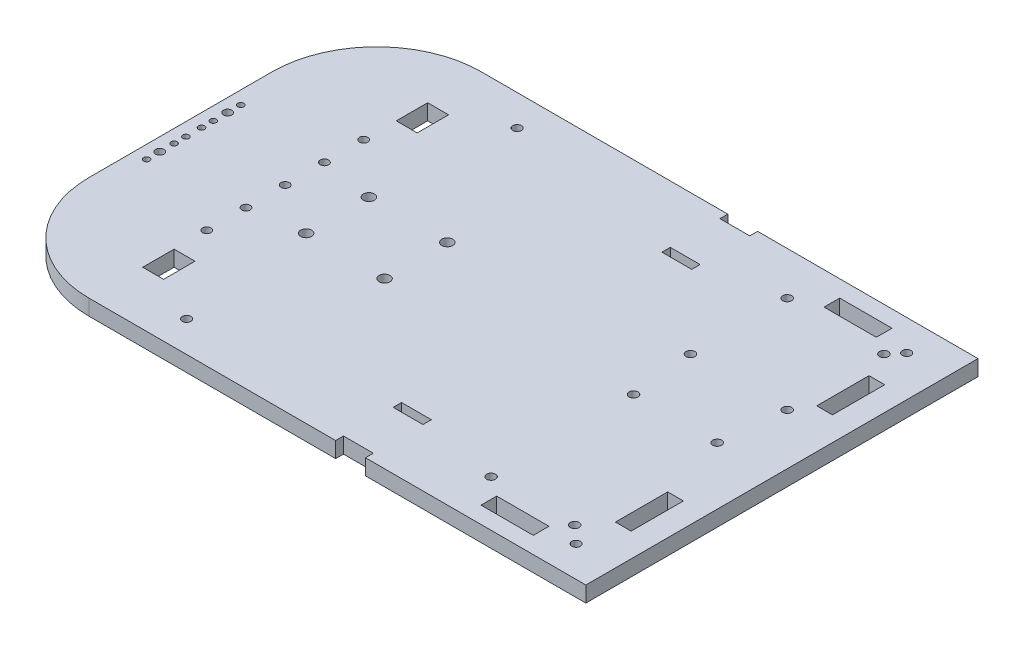
SolidWorks part; units mm, degrees
ref_plane "Front Plane" through (0, 0, 0) normal (0, 0, 1) x (1, 0, 0)
ref_plane "Top Plane" through (0, 0, 0) normal (0, 1, 0) x (1, 0, 0)
ref_plane "Right Plane" through (0, 0, 0) normal (1, 0, 0) x (0, 0, -1)
sketch "Sketch1" plane through (0, 0, 0) normal (0, 1, 0) x (1, 0, 0)
  line L1 (-115, 75) -> (115, 75)
  line L2 (-115, 75) -> (-115, -75)
  line L3 (-115, -75) -> (115, -75)
  line L4 (115, 75) -> (115, -75)
  line L5 (-115, 75) -> (115, -75) construction
  line L6 (-115, -75) -> (115, 75) construction
  point P0 (0, 0)
  dimension "D1" = 230
  dimension "D2" = 150
extrude "Boss-Extrude1" add sketch "Sketch1" along normal blind 6
sketch "Sketch2" plane through (0, 6, 0) normal (0, 1, 0) x (1, 0, 0)
  line L0 (115, 0) -> (-142.2059, 0) construction
  line L1 (115, -75) -> (115, 75) construction
  line L2 (-115, 0) -> (-80, 0) construction
  line L4 (-115, 75) -> (-115, -75) construction
  line L5 (115, 0) -> (25, 0) construction
  line L6 (25, 0) -> (25, -48.4236) construction
  line L7 (25, -75) -> (25, -72) construction
  line L8 (19.3, -72) -> (30.7, -72)
  line L9 (-115, -75) -> (115, -75) construction
  line L10 (25, -72) -> (25, -53) construction
  line L11 (19.3, -72) -> (19.3, -75)
  line L12 (19.3, -49.8) -> (30.7, -49.8)
  line L13 (19.3, -49.8) -> (19.3, -53)
  line L14 (19.3, -53) -> (30.7, -53)
  line L15 (30.7, -49.8) -> (30.7, -53)
  line L16 (19.3, -49.8) -> (30.7, -53) construction
  line L17 (19.3, -53) -> (30.7, -49.8) construction
  line L18 (19.3, -75) -> (30.7, -75)
  line L19 (30.7, -72) -> (30.7, -75)
  line L20 (19.3, -72) -> (30.7, -75) construction
  line L21 (19.3, -75) -> (30.7, -72) construction
  point P7 (25, -73.5)
  point P16 (25, -51.4)
  point P22 (25, -53)
  point P27 (25, -72)
  dimension "D1" = 35
  dimension "D2" = 90
  dimension "D3" = 3
  dimension "D4" = 19
  dimension "D5" = 3.2
  dimension "D6" = 11.4
  dimension "D7" = 3
  dimension "D8" = 11.4
extrude "Cut-Extrude1" cut sketch "Sketch2" against normal blind 26
mirror "Mirror1" about plane through (0, 0, 0) normal (0, 0, 1) of "Cut-Extrude1"
sketch "Sketch3" plane through (0, 6, 0) normal (0, 1, 0) x (1, 0, 0)
  line L0 (-115, 0) -> (112.5797, 0) construction
  line L1 (-115, 75) -> (-115, -75) construction
  line L3 (-55, 12) -> (-25, 12) construction
  line L4 (-55, 12) -> (-55, -12) construction
  line L5 (-55, -12) -> (-25, -12) construction
  line L6 (-25, 12) -> (-25, -12) construction
  line L7 (-55, 12) -> (-25, -12) construction
  line L8 (-55, -12) -> (-25, 12) construction
  circle A0 centre (-25, -12) radius 2.1
  circle A1 centre (-25, 12) radius 2.1
  circle A2 centre (-55, 12) radius 2.1
  circle A3 centre (-55, -12) radius 2.1
  point P5 (-40, 0)
  dimension "D4" = 4.2
  dimension "D5" = 4.2
  dimension "D1" = 30
  dimension "D2" = 24
  dimension "D3" = 60
extrude "Cut-Extrude2" cut sketch "Sketch3" against normal blind 26
sketch "Sketch4" plane through (0, 6, 0) normal (0, 1, 0) x (1, 0, 0)
  line L0 (-115, 0) -> (-75, 0) construction
  line L1 (-115, 75) -> (-115, -75) construction
  line L2 (-75, 37.5) -> (-75, -37.5) construction
  circle A0 centre (-75, 0) radius 1.6
  circle A1 centre (-75, 15) radius 1.6
  circle A2 centre (-75, 30) radius 1.6
  point P7 (-75, 0)
  dimension "D3" = 3.2
  dimension "D4" = 3.2
  dimension "D6" = 3.2
  dimension "D1" = 40
  dimension "D2" = 75
  dimension "D5" = 15
  dimension "D7" = 15
extrude "Cut-Extrude3" cut sketch "Sketch4" against normal blind 26
mirror "Mirror2" about plane through (0, 0, 0) normal (0, 0, 1) of "Cut-Extrude3"
sketch "Sketch5" plane through (0, 6, 0) normal (0, 1, 0) x (1, 0, 0)
  line L0 (-75, 0) -> (-110, 0) construction
  line L3 (-110, 10.25) -> (-110, -10.25) construction
  circle A0 centre (-110, 7.5) radius 1.175
  circle A1 centre (-110, -7.5) radius 1.175
  point P2 (-110, 0)
  dimension "D3" = 2.35
  dimension "D1" = 35
  dimension "D2" = 20.5
  dimension "D4" = 7.5
extrude "Cut-Extrude4" cut sketch "Sketch5" against normal blind 26
sketch "Sketch6" plane through (0, 6, 0) normal (0, 1, 0) x (1, 0, 0)
  line L1 (-110, 10) -> (-110, -10) construction
  line L2 (-75, 0) -> (-110, 0) construction
  line L3 (-75, 0) -> (-110, 0) construction
  circle A0 centre (-110, 3) radius 1.175
  circle A1 centre (-110, 18) radius 1.175
  point P4 (-110, 0)
  dimension "D2" = 2.35
  dimension "D4" = 2.35
  dimension "D1" = 20
  dimension "D3" = 3
  dimension "D5" = 15
extrude "Cut-Extrude5" cut sketch "Sketch6" against normal blind 26
mirror "Mirror3" about plane through (0, 0, 0) normal (0, 0, 1) of "Cut-Extrude5"
sketch "Sketch7" plane through (0, 6, 0) normal (0, 1, 0) x (1, 0, 0)
  line L0 (-115, 0) -> (-75, 0) construction
  line L1 (-115, 75) -> (-115, -75) construction
  line L2 (-75, 0) -> (-75, 42.5) construction
  line L4 (-75, 42.5) -> (-67, 42.5)
  line L5 (-75, 42.5) -> (-75, 54.5)
  line L6 (-75, 54.5) -> (-67, 54.5)
  line L7 (-67, 42.5) -> (-67, 54.5)
  dimension "D1" = 42.5
  dimension "D2" = 12
  dimension "D3" = 8
extrude "Cut-Extrude6" cut sketch "Sketch7" against normal blind 26
mirror "Mirror4" about plane through (0, 0, 0) normal (0, 0, 1) of "Cut-Extrude6"
fillet "Fillet1" radius 40 2 edges at (-115, 3, -75) (-115, 3, 75)
sketch "Sketch8" plane through (0, 6, 0) normal (0, 1, 0) x (1, 0, 0)
  line L0 (0, 0) -> (25, 0) construction
  line L1 (-57.5, 70) -> (-49.5, 70) construction
  line L2 (-57.5, 70) -> (107.5, 70) construction
  line L3 (-57.5, 70) -> (-57.5, -70) construction
  line L4 (-57.5, -70) -> (107.5, -70) construction
  line L5 (107.5, 70) -> (107.5, -70) construction
  line L6 (-57.5, 70) -> (107.5, -70) construction
  line L7 (-57.5, -70) -> (107.5, 70) construction
  line L8 (-49.5, 70) -> (-49.5, 63.2121) construction
  line L9 (25, 0) -> (25, 30.5457) construction
  line L10 (25, 0) -> (47.2283, 0) construction
  circle A0 centre (-49.5, 63.2121) radius 1.65
  circle A2 centre (-49.5, -63.2121) radius 1.65
  circle A3 centre (99.5, -63.2121) radius 1.65
  circle A4 centre (99.5, 63.2121) radius 1.65
  dimension "D5" = 3.3
  dimension "D1" = 25
  dimension "D2" = 165
  dimension "D3" = 140
  dimension "D4" = 8
extrude "Cut-Extrude7" cut sketch "Sketch8" against normal blind 26
sketch "Sketch9" plane through (0, 6, 0) normal (0, 1, 0) x (1, 0, 0)
  line L0 (-115, 0) -> (-90.6898, 0) construction
  line L1 (-115, 35) -> (-115, -35) construction
  line L2 (-110, -7.5) -> (-110, -14.3971) construction
  circle A0 centre (-110, -13) radius 1.6
  dimension "D2" = 3.2
  dimension "D1" = 13
extrude "Cut-Extrude8" cut sketch "Sketch9" against normal blind 10
mirror "Mirror5" about plane through (0, 0, 0) normal (0, 0, 1) of "Cut-Extrude8"
sketch "Sketch10" plane through (0, 6, 0) normal (0, 1, 0) x (1, 0, 0)
  line L1 (-17.5, 37.5) -> (47.5, 37.5) construction
  line L2 (-17.5, 37.5) -> (-17.5, -37.5) construction
  line L3 (-17.5, -37.5) -> (47.5, -37.5) construction
  line L4 (47.5, 37.5) -> (47.5, -37.5) construction
  line L5 (-17.5, 37.5) -> (47.5, -37.5) construction
  line L6 (-17.5, -37.5) -> (47.5, 37.5) construction
  line L7 (58.5, 58.5) -> (95.5, 58.5) construction
  line L8 (58.5, 58.5) -> (58.5, 21.5) construction
  line L9 (58.5, 21.5) -> (95.5, 21.5) construction
  line L10 (95.5, 58.5) -> (95.5, 21.5) construction
  line L11 (58.5, 58.5) -> (95.5, 21.5) construction
  line L12 (58.5, 21.5) -> (95.5, 58.5) construction
  line L13 (61, -2.75) -> (93, -2.75) construction
  line L14 (61, -2.75) -> (61, -57.25) construction
  line L15 (61, -57.25) -> (93, -57.25) construction
  line L16 (93, -2.75) -> (93, -57.25) construction
  line L17 (61, -2.75) -> (93, -57.25) construction
  line L18 (61, -57.25) -> (93, -2.75) construction
  circle A0 centre (58.5, 21.5) radius 1.7
  circle A1 centre (95.5, 21.5) radius 1.7
  circle A2 centre (95.5, 58.5) radius 1.7
  circle A3 centre (58.5, 58.5) radius 1.7
  circle A4 centre (61, -2.75) radius 1.7
  circle A5 centre (93, -2.75) radius 1.7
  circle A6 centre (61, -57.25) radius 1.7
  circle A7 centre (93, -57.25) radius 1.7
  point P0 (15, 0)
  point P6 (77, 40)
  point P15 (77, -30)
  dimension "D8" = 3.4
  dimension "D9" = 54.5
  dimension "D1" = 75
  dimension "D2" = 15
  dimension "D3" = 65
  dimension "D4" = 37
  dimension "D5" = 37
  dimension "D6" = 62
  dimension "D7" = 40
  dimension "D10" = 32
  dimension "D11" = 62
  dimension "D12" = 30
extrude "Cut-Extrude9" cut sketch "Sketch10" against normal blind 10
sketch "Sketch12" plane through (0, 6, 0) normal (0, 1, 0) x (1, 0, 0)
  line L5 (68.5, 68.606) -> (88.5, 68.606)
  line L6 (68.5, 68.606) -> (68.5, 62.606)
  line L7 (68.5, 62.606) -> (88.5, 62.606)
  line L8 (88.5, 68.606) -> (88.5, 62.606)
  line L9 (99.8155, 48.5) -> (105.8155, 48.5)
  line L10 (99.8155, 48.5) -> (99.8155, 28.5)
  line L11 (99.8155, 28.5) -> (105.8155, 28.5)
  line L12 (105.8155, 48.5) -> (105.8155, 28.5)
  circle A1 centre (58.5, 58.5) radius 1.7 construction
  circle A2 centre (95.5, 58.5) radius 1.7 construction
  point P8 (78.5, 62.606)
  point P13 (99.8155, 38.5)
  dimension "D1" = 20
  dimension "D2" = 6
  dimension "D3" = 20
  dimension "D4" = 20
  dimension "D5" = 20
  dimension "D6" = 6
extrude "Cut-Extrude10" cut sketch "Sketch12" against normal blind 10
mirror "Mirror6" about plane through (0, 0, 0) normal (0, 0, 1) of "Cut-Extrude10"
